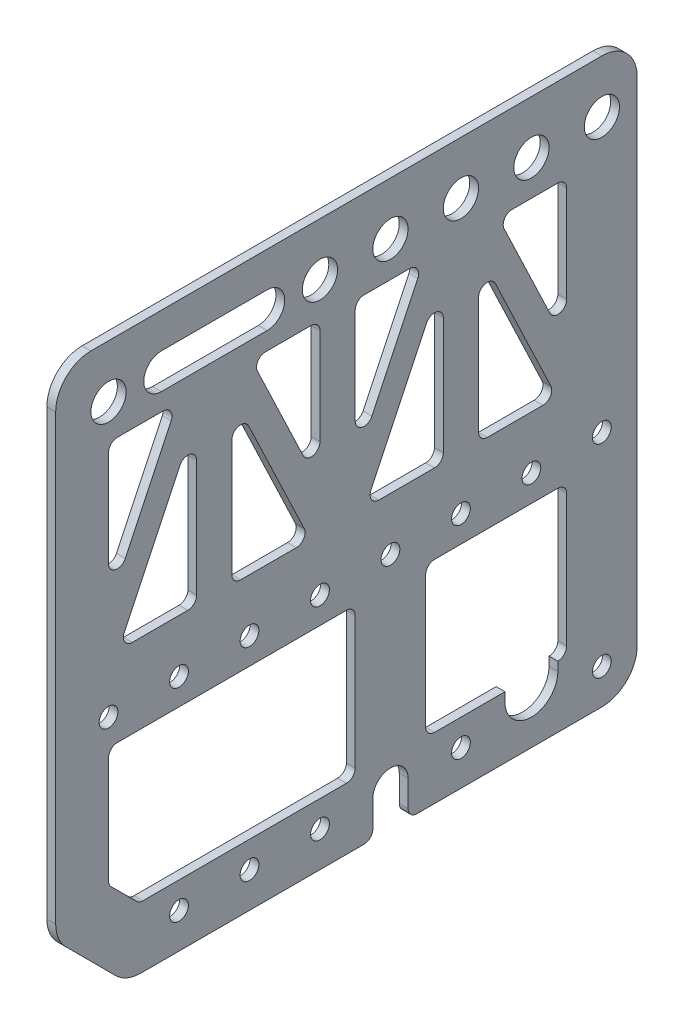
SolidWorks part; units mm, degrees
material "6061-T6 (SS)"
ref_plane "Front Plane" through (0, 0, 0) normal (0, 0, 1) x (1, 0, 0)
ref_plane "Top Plane" through (0, 0, 0) normal (0, 1, 0) x (1, 0, 0)
ref_plane "Right Plane" through (0, 0, 0) normal (1, 0, 0) x (0, 0, -1)
sketch "Sketch1" plane through (0, 0, 0) normal (1, 0, 0) x (0, 0, -1)
  line L0 (0, 0) -> (0, 203.2)
  line L1 (0, 203.2) -> (-209.55, 203.2)
  line L2 (-82.55, 12.7) -> (-82.55, 3.175)
  line L3 (-209.55, 203.2) -> (-209.55, 25.4)
  line L4 (-184.15, 0) -> (-98.425, 0)
  line L5 (-12.7, 85.725) -> (-38.1, 85.725) construction
  line L6 (-12.7, 184.15) -> (-38.1, 184.15) construction
  line L7 (-95.25, 12.7) -> (-95.25, 3.175)
  line L8 (-79.375, 0) -> (0, 0)
  line L9 (-209.55, 25.4) -> (-184.15, 0)
  line L10 (-57.15, 164.0651) -> (-57.15, 171.45) construction
  line L11 (-76.2, 73.025) -> (-76.2, 25.4)
  line L12 (-73.025, 22.225) -> (-47.625, 22.225)
  line L13 (-25.4, 25.4) -> (-25.4, 73.025)
  line L14 (-28.575, 76.2) -> (-73.025, 76.2)
  line L15 (-33.9451, 104.775) -> (-53.975, 104.775)
  line L16 (-25.4, 133.5971) -> (-25.4, 168.275)
  line L17 (-28.575, 22.225) -> (-28.575, 19.05)
  line L18 (-47.625, 22.225) -> (-47.625, 19.05)
  line L19 (-133.35, 184.15) -> (-171.45, 184.15) construction
  line L20 (-180.3642, 23.1549) -> (-189.5701, 32.3608)
  line L21 (-187.325, 76.2) -> (-104.775, 76.2)
  line L22 (-190.5, 34.6059) -> (-190.5, 73.025)
  line L23 (-178.1191, 22.225) -> (-104.775, 22.225)
  line L24 (-101.6, 73.025) -> (-101.6, 25.4)
  line L25 (-28.575, 171.45) -> (-45.0883, 171.45)
  line L26 (-57.15, 107.95) -> (-57.15, 150.0128)
  line L27 (-51.1084, 151.3778) -> (-31.0785, 109.315)
  line L28 (-47.9549, 166.91) -> (-31.4416, 132.232)
  line L29 (-57.15, 171.45) -> (-50.1168, 171.45) construction
  line L30 (-25.4, 119.5447) -> (-25.4, 104.775) construction
  line L31 (-25.4, 104.775) -> (-28.9166, 104.775) construction
  line L32 (-57.15, 171.45) -> (-25.4, 104.775) construction
  line L33 (-63.5, 184.15) -> (-63.5, 85.725) construction
  line L34 (-69.85, 171.45) -> (-101.6, 104.775) construction
  line L35 (-101.6, 104.775) -> (-98.0834, 104.775) construction
  line L36 (-101.6, 119.5447) -> (-101.6, 104.775) construction
  line L37 (-69.85, 171.45) -> (-76.8832, 171.45) construction
  line L38 (-69.85, 164.0651) -> (-69.85, 171.45) construction
  line L39 (-79.0451, 166.91) -> (-95.5584, 132.232)
  line L40 (-75.8916, 151.3778) -> (-95.9215, 109.315)
  line L41 (-69.85, 107.95) -> (-69.85, 150.0128)
  line L42 (-98.425, 171.45) -> (-81.9117, 171.45)
  line L43 (-101.6, 133.5971) -> (-101.6, 168.275)
  line L44 (-93.0549, 104.775) -> (-73.025, 104.775)
  line L45 (-122.8451, 104.775) -> (-142.875, 104.775)
  line L46 (-114.3, 133.5971) -> (-114.3, 168.275)
  line L47 (-117.475, 171.45) -> (-133.9883, 171.45)
  line L48 (-146.05, 107.95) -> (-146.05, 150.0128)
  line L49 (-140.0084, 151.3778) -> (-119.9785, 109.315)
  line L50 (-136.8549, 166.91) -> (-120.3416, 132.232)
  line L51 (-167.9451, 166.91) -> (-184.4584, 132.232)
  line L52 (-164.7916, 151.3778) -> (-184.8215, 109.315)
  line L53 (-158.75, 107.95) -> (-158.75, 150.0128)
  line L54 (-187.325, 171.45) -> (-170.8117, 171.45)
  line L55 (-190.5, 133.5971) -> (-190.5, 168.275)
  line L56 (-181.9549, 104.775) -> (-161.925, 104.775)
  line L57 (-146.05, 164.0651) -> (-146.05, 171.45) construction
  line L58 (-146.05, 171.45) -> (-139.0168, 171.45) construction
  line L59 (-114.3, 119.5447) -> (-114.3, 104.775) construction
  line L60 (-114.3, 104.775) -> (-117.8166, 104.775) construction
  line L61 (-146.05, 171.45) -> (-114.3, 104.775) construction
  line L62 (-158.75, 171.45) -> (-190.5, 104.775) construction
  line L63 (-190.5, 104.775) -> (-186.9834, 104.775) construction
  line L64 (-190.5, 119.5447) -> (-190.5, 104.775) construction
  line L65 (-158.75, 171.45) -> (-165.7832, 171.45) construction
  line L66 (-158.75, 164.0651) -> (-158.75, 171.45) construction
  line L67 (-152.4, 184.15) -> (-152.4, 85.725) construction
  line L68 (-33.9451, 104.775) -> (-122.8451, 104.775) construction
  line L69 (-133.35, 177.8) -> (-171.45, 177.8)
  line L70 (-133.35, 190.5) -> (-171.45, 190.5)
  circle A0 centre (-12.7, 12.7) radius 3.3782
  arc A1 (-51.1084, 151.3778) -> (-57.15, 150.0128) centre (-53.975, 150.0128) ccw
  circle A2 centre (-63.5, 12.7) radius 3.3782
  arc A3 (-82.55, 12.7) -> (-95.25, 12.7) centre (-88.9, 12.7) ccw
  circle A4 centre (-114.3, 12.7) radius 3.3782
  circle A5 centre (-12.7, 85.725) radius 3.3782
  circle A6 centre (-38.1, 85.725) radius 3.3782
  circle A7 centre (-63.5, 85.725) radius 3.3782
  circle A8 centre (-88.9, 85.725) radius 3.3782
  arc A9 (-95.25, 3.175) -> (-98.425, 0) centre (-98.425, 3.175) cw
  circle A10 centre (-12.7, 184.15) radius 6.35
  circle A11 centre (-38.1, 184.15) radius 6.35
  circle A12 centre (-63.5, 184.15) radius 6.35
  circle A13 centre (-88.9, 184.15) radius 6.35
  circle A14 centre (-114.3, 184.15) radius 6.35
  circle A15 centre (-139.7, 184.15) radius 6.35 construction
  circle A16 centre (-165.1, 184.15) radius 6.35 construction
  circle A17 centre (-190.5, 184.15) radius 6.35
  arc A18 (-82.55, 3.175) -> (-79.375, 0) centre (-79.375, 3.175) ccw
  arc A19 (-47.625, 19.05) -> (-28.575, 19.05) centre (-38.1, 19.05) ccw
  circle A20 centre (-139.7, 12.7) radius 3.3782
  circle A21 centre (-165.1, 12.7) radius 3.3782
  arc A22 (-53.975, 104.775) -> (-57.15, 107.95) centre (-53.975, 107.95) cw
  arc A23 (-133.35, 177.8) -> (-133.35, 190.5) centre (-133.35, 184.15) ccw
  arc A24 (-171.45, 190.5) -> (-171.45, 177.8) centre (-171.45, 184.15) ccw
  circle A25 centre (-114.3, 85.725) radius 3.3782
  circle A26 centre (-139.7, 85.725) radius 3.3782
  circle A27 centre (-165.1, 85.725) radius 3.3782
  circle A28 centre (-190.5, 85.725) radius 3.3782
  circle A29 centre (-88.9, 12.7) radius 3.3782 [skipped]
  circle A30 centre (-38.1, 12.7) radius 3.3782 [skipped]
  arc A31 (-28.575, 22.225) -> (-25.4, 25.4) centre (-28.575, 25.4) ccw
  arc A32 (-76.2, 25.4) -> (-73.025, 22.225) centre (-73.025, 25.4) ccw
  arc A33 (-25.4, 73.025) -> (-28.575, 76.2) centre (-28.575, 73.025) ccw
  arc A34 (-73.025, 76.2) -> (-76.2, 73.025) centre (-73.025, 73.025) ccw
  arc A35 (-189.5701, 32.3608) -> (-190.5, 34.6059) centre (-187.325, 34.6059) cw
  arc A36 (-180.3642, 23.1549) -> (-178.1191, 22.225) centre (-178.1191, 25.4) ccw
  arc A37 (-104.775, 22.225) -> (-101.6, 25.4) centre (-104.775, 25.4) ccw
  arc A38 (-104.775, 76.2) -> (-101.6, 73.025) centre (-104.775, 73.025) cw
  arc A39 (-190.5, 73.025) -> (-187.325, 76.2) centre (-187.325, 73.025) cw
  arc A40 (-31.0785, 109.315) -> (-33.9451, 104.775) centre (-33.9451, 107.95) cw
  arc A41 (-31.4416, 132.232) -> (-25.4, 133.5971) centre (-28.575, 133.5971) ccw
  arc A42 (-25.4, 168.275) -> (-28.575, 171.45) centre (-28.575, 168.275) ccw
  arc A43 (-47.9549, 166.91) -> (-45.0883, 171.45) centre (-45.0883, 168.275) cw
  arc A44 (-79.0451, 166.91) -> (-81.9117, 171.45) centre (-81.9117, 168.275) ccw
  arc A45 (-101.6, 168.275) -> (-98.425, 171.45) centre (-98.425, 168.275) cw
  arc A46 (-95.5584, 132.232) -> (-101.6, 133.5971) centre (-98.425, 133.5971) cw
  arc A47 (-95.9215, 109.315) -> (-93.0549, 104.775) centre (-93.0549, 107.95) ccw
  arc A48 (-73.025, 104.775) -> (-69.85, 107.95) centre (-73.025, 107.95) ccw
  arc A49 (-75.8916, 151.3778) -> (-69.85, 150.0128) centre (-73.025, 150.0128) cw
  arc A50 (-140.0084, 151.3778) -> (-146.05, 150.0128) centre (-142.875, 150.0128) ccw
  arc A51 (-142.875, 104.775) -> (-146.05, 107.95) centre (-142.875, 107.95) cw
  arc A52 (-119.9785, 109.315) -> (-122.8451, 104.775) centre (-122.8451, 107.95) cw
  arc A53 (-120.3416, 132.232) -> (-114.3, 133.5971) centre (-117.475, 133.5971) ccw
  arc A54 (-114.3, 168.275) -> (-117.475, 171.45) centre (-117.475, 168.275) ccw
  arc A55 (-136.8549, 166.91) -> (-133.9883, 171.45) centre (-133.9883, 168.275) cw
  arc A56 (-167.9451, 166.91) -> (-170.8117, 171.45) centre (-170.8117, 168.275) ccw
  arc A57 (-190.5, 168.275) -> (-187.325, 171.45) centre (-187.325, 168.275) cw
  arc A58 (-184.4584, 132.232) -> (-190.5, 133.5971) centre (-187.325, 133.5971) cw
  arc A59 (-184.8215, 109.315) -> (-181.9549, 104.775) centre (-181.9549, 107.95) ccw
  arc A60 (-161.925, 104.775) -> (-158.75, 107.95) centre (-161.925, 107.95) ccw
  arc A61 (-164.7916, 151.3778) -> (-158.75, 150.0128) centre (-161.925, 150.0128) cw
  point P56 (-82.55, 0)
  point P76 (-152.4, 184.15)
  point P78 (-28.575, 22.225)
  dimension "D6" = 6.7564
  dimension "D14" = 12.7
  dimension "D18" = 25.4
  dimension "D20" = 25.4
  dimension "D3" = 12.7
  dimension "D17" = 3.175
  dimension "D24" = 19.05
  dimension "D27" = 38.1
  dimension "D31" = 3.175
  dimension "D37" = 2
  dimension "D36" = 3.175
  dimension "D1" = 203.2
  dimension "D2" = 209.55
  dimension "D4" = 12.7
  dimension "D5" = 12.7
  dimension "D7" = 12.7
  dimension "D9" = 25.4
  dimension "D10" = 73.025
  dimension "D12" = 6.35
  dimension "D13" = 184.15
  dimension "D16" = 25.4
  dimension "D19" = 25.4
  dimension "D21" = 12.7
  dimension "D22" = 9.525
  dimension "D23" = 9.525
  dimension "D25" = 19.05
  dimension "D26" = 38.1
  dimension "D28" = 12.7
  dimension "D29" = 19.05
  dimension "D30" = 19.05
  dimension "D32" = 12.7
  dimension "D33" = 19.05
  dimension "D34" = 3.175
  dimension "D35" = 31.75
  dimension "D38" = 88.9
  dimension "D8" = 7
  dimension "D11" = 8
  dimension "D15" = 8
extrude "Boss-Extrude1" add sketch "Sketch1" along normal mid plane 3.175
fillet "Fillet1" radius 12.7 5 edges at (0, 203.2, 0) (0, 203.2, 209.55) (0, 0, 0) (0, 0, 184.15) (0, 25.4, 209.55)
